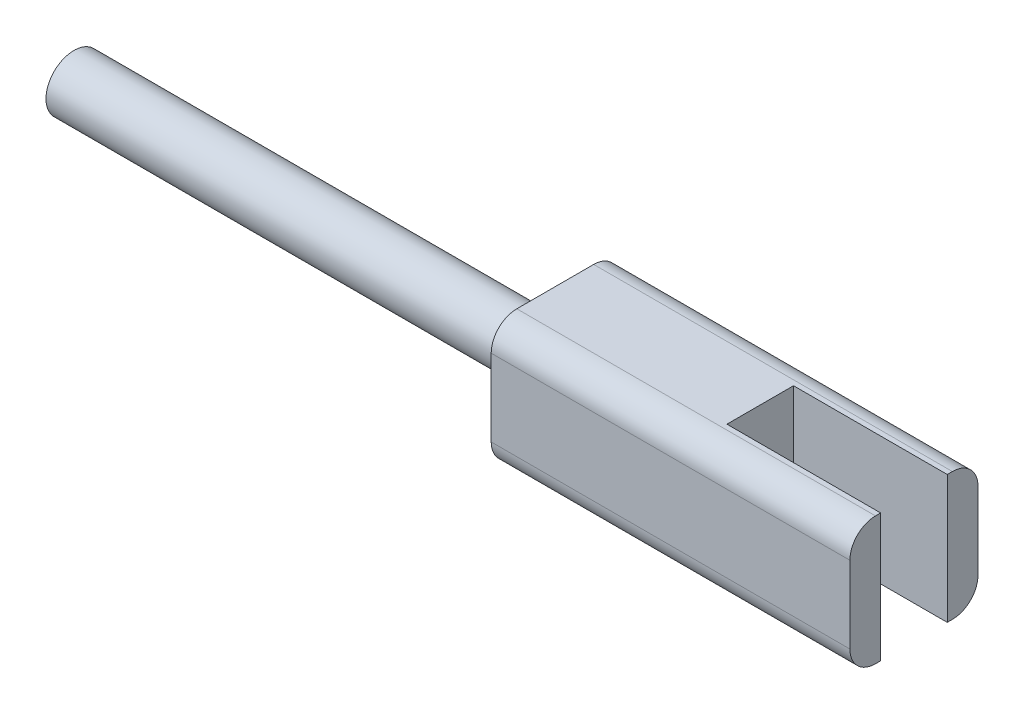
SolidWorks part; units mm, degrees
ref_plane "Front Plane" through (0, 0, 0) normal (0, 0, 1) x (1, 0, 0)
ref_plane "Top Plane" through (0, 0, 0) normal (0, 1, 0) x (1, 0, 0)
ref_plane "Right Plane" through (0, 0, 0) normal (1, 0, 0) x (0, 0, -1)
sketch "Sketch1" plane through (0, 0, 0) normal (1, 0, 0) x (0, 0, -1)
  circle A0 centre (0, 0) radius 1.09
extrude "Boss-Extrude1" add sketch "Sketch1" along normal blind 20.786
ref_plane "Plane1" through (18.786, 0, 0) normal (1, 0, 0) x (0, 0, -1)
sketch "Sketch2" plane through (18.786, 0, 0) normal (1, 0, 0) x (0, 0, -1)
  line L0 (-1.5, -2.5) -> (1.5, -2.5)
  line L1 (2.5, -1.5) -> (2.5, 1.5)
  line L2 (1.5, 2.5) -> (-1.5, 2.5)
  line L3 (-2.5, 1.5) -> (-2.5, -1.5)
  arc A0 (1.5, -2.5) -> (2.5, -1.5) centre (1.5, -1.5) ccw
  arc A1 (2.5, 1.5) -> (1.5, 2.5) centre (1.5, 1.5) ccw
  arc A2 (-1.5, 2.5) -> (-2.5, 1.5) centre (-1.5, 1.5) ccw
  arc A3 (-2.5, -1.5) -> (-1.5, -2.5) centre (-1.5, -1.5) ccw
extrude "Boss-Extrude2" add sketch "Sketch2" along normal blind 14
sketch "Sketch3" plane through (0, 0, 0) normal (0, 1, 0) x (1, 0, 0)
  line L0 (26.786, 1.3) -> (33.786, 1.3)
  line L1 (33.786, 1.3) -> (33.786, -1.3)
  line L2 (33.786, -1.3) -> (26.786, -1.3)
  line L3 (26.786, -1.3) -> (26.786, 1.3)
extrude "Cut-Extrude1" cut sketch "Sketch3" against normal through all and the other way through all
